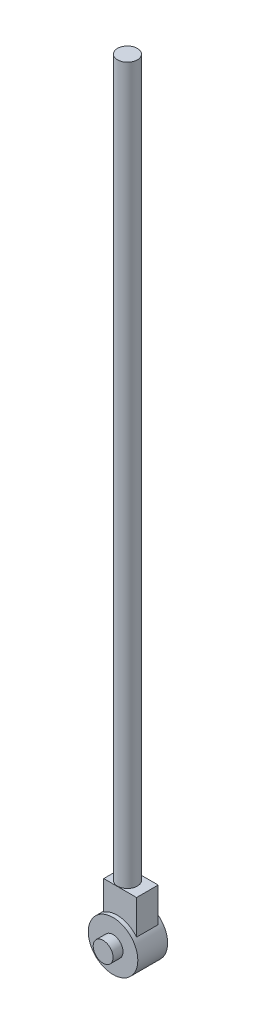
SolidWorks part; units mm, degrees
ref_plane "Front Plane" through (0, 0, 0) normal (0, 0, 1) x (1, 0, 0)
ref_plane "Top Plane" through (0, 0, 0) normal (0, 1, 0) x (1, 0, 0)
ref_plane "Right Plane" through (0, 0, 0) normal (1, 0, 0) x (0, 0, -1)
sketch "Sketch1" plane through (0, 0, 0) normal (0, 0, 1) x (1, 0, 0)
  circle A0 centre (0, 0) radius 2.49
  dimension "D1" = 4.98
extrude "Boss-Extrude1" add sketch "Sketch1" along normal blind 3
sketch "Sketch2" plane through (0, 0, 3) normal (0, 0, 1) x (1, 0, 0)
  circle A0 centre (0, 0) radius 1
extrude "Boss-Extrude2" add sketch "Sketch2" against normal blind 4 and the other way blind 1
sketch "Sketch3" plane through (0, 0, 0) normal (0, 1, 0) x (1, 0, 0)
  line L1 (-1.3516, -0.4115) -> (1.9522, -0.4115)
  line L2 (-1.3516, -0.4115) -> (-1.3516, -2.5885)
  line L3 (-1.3516, -2.5885) -> (1.9522, -2.5885)
  line L4 (1.9522, -0.4115) -> (1.9522, -2.5885)
  line L5 (-1.3516, -0.4115) -> (1.9522, -2.5885) construction
  line L6 (-1.3516, -2.5885) -> (1.9522, -0.4115) construction
  point P0 (0.3003, -1.5)
extrude "Boss-Extrude3" add sketch "Sketch3" along normal blind 5
sketch "Sketch4" plane through (0, 5, 0) normal (0, 1, 0) x (1, 0, 0)
  circle A0 centre (0, -1.5556) radius 1
extrude "Boss-Extrude4" add sketch "Sketch4" along normal blind 72
